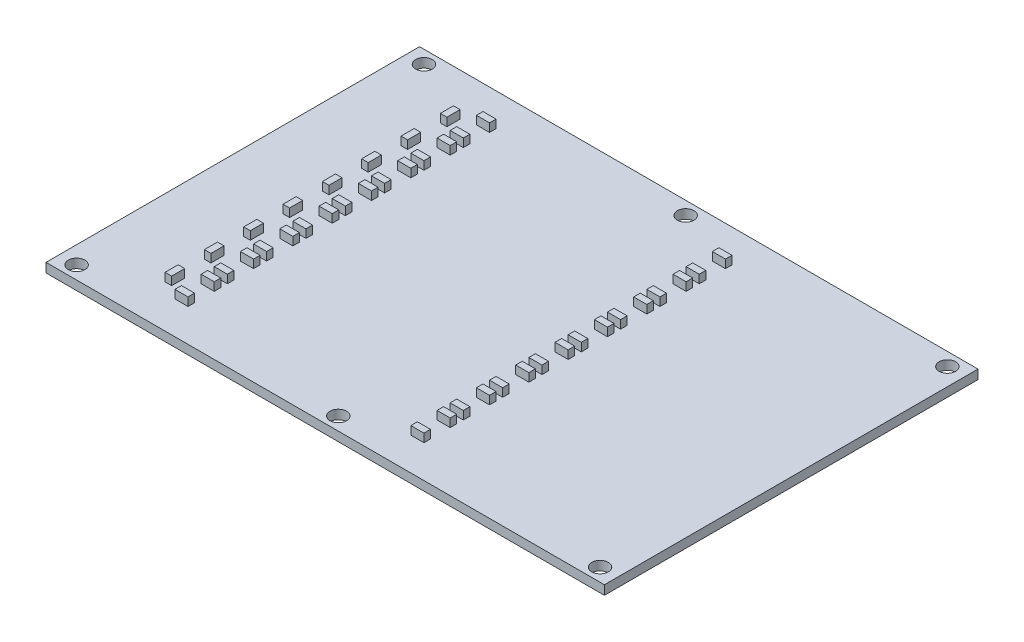
SolidWorks part; units mm, degrees
ref_plane "Front" through (0, 0, 0) normal (0, 0, 1) x (1, 0, 0)
ref_plane "Top" through (0, 0, 0) normal (0, 1, 0) x (1, 0, 0)
ref_plane "Right" through (0, 0, 0) normal (1, 0, 0) x (0, 0, -1)
sketch "Sketch1" plane through (0, 0, 0) normal (0, 1, 0) x (1, 0, 0)
  line L1 (0, 0) -> (127.8, 0)
  line L2 (0, 0) -> (0, 85.5)
  line L3 (0, 85.5) -> (127.8, 85.5)
  line L4 (127.8, 0) -> (127.8, 85.5)
  dimension "D1" = 127.8
  dimension "D2" = 85.5
extrude "Boss-Extrude1" add sketch "Sketch1" along normal blind 2.1
sketch "Sketch2" plane through (0, 2.1, 0) normal (0, 1, 0) x (1, 0, 0)
  line L0 (0, 85.5) -> (0, 0) construction
  line L1 (0, 0) -> (127.8, 0) construction
  circle A0 centre (4, 3) radius 1.9
  dimension "D3" = 3.8
  dimension "D1" = 4
  dimension "D2" = 3
extrude "Cut-Extrude1" cut sketch "Sketch2" against normal through all
pattern_linear "LPattern1" count 3 spacing 59.9 along (1, 0, 0) of "Cut-Extrude1"
ref_plane "Plane1" through (0, 0, -42.75) normal (0, 0, 1) x (1, 0, 0)
mirror "Mirror1" about plane through (0, 0, -42.75) normal (0, 0, 1) of "LPattern1", "Cut-Extrude1"
sketch "Sketch3" plane through (0, 2.1, 0) normal (0, 1, 0) x (1, 0, 0)
  line L0 (0, 42.75) -> (127.8, 42.75) construction
  line L1 (0, 85.5) -> (0, 0) construction
  line L2 (127.8, 0) -> (127.8, 85.5) construction
  line L3 (63.9, 85.5) -> (63.9, 0) construction
  line L4 (127.8, 85.5) -> (0, 85.5) construction
  line L5 (0, 0) -> (127.8, 0) construction
  line L6 (77.5, 40.5) -> (77.5, 36) construction
  line L7 (76, 42) -> (79, 42)
  line L8 (76, 42) -> (76, 40.5)
  line L9 (76, 40.5) -> (79, 40.5)
  line L10 (79, 42) -> (79, 40.5)
  line L11 (77.5, 38.25) -> (63.104, 38.25) construction
  line L12 (76, 36) -> (79, 36)
  line L13 (76, 36) -> (76, 34.5)
  line L14 (76, 34.5) -> (79, 34.5)
  line L15 (79, 36) -> (79, 34.5)
  point P22 (77.5, 36)
  dimension "D1" = 1.5
  dimension "D2" = 3
  dimension "D3" = 15.1
  dimension "D4" = 1.5
  dimension "D5" = 3
  dimension "D6" = 4.5
  dimension "D7" = 4.5
extrude "Boss-Extrude2" add sketch "Sketch3" along normal blind 1.9
pattern_linear "LPattern2" count 4 spacing 9 along (0, 0, 1) of "Boss-Extrude2"
mirror "Mirror2" about plane through (0, 0, -42.75) normal (0, 0, 1) of "Boss-Extrude2", "LPattern2"
pattern_linear "LPattern3" count 2 spacing 54 along (-1, 0, 0) of "Mirror2", "Boss-Extrude2", "LPattern2"
sketch "Sketch4" plane through (0, 2.1, 0) normal (0, 1, 0) x (1, 0, 0)
  line L0 (23.5, 76.5) -> (23.5, 72) construction
  line L1 (17.5, 75.75) -> (19, 75.75)
  line L2 (17.5, 75.75) -> (17.5, 72.75)
  line L3 (17.5, 72.75) -> (19, 72.75)
  line L4 (19, 75.75) -> (19, 72.75)
  line L5 (25, 76.5) -> (22, 76.5) construction
  line L6 (22, 72) -> (25, 72) construction
  line L7 (23.5, 74.25) -> (9.1207, 74.25) construction
  line L8 (18.25, 72.75) -> (18.25, 70.2152) construction
  point P12 (19, 74.25)
  dimension "D1" = 1.5
  dimension "D2" = 3
  dimension "D3" = 5.25
extrude "Boss-Extrude3" add sketch "Sketch4" along normal blind 1.9
pattern_linear "LPattern4" count 8 spacing 9 along (0, 0, 1) of "Boss-Extrude3"
